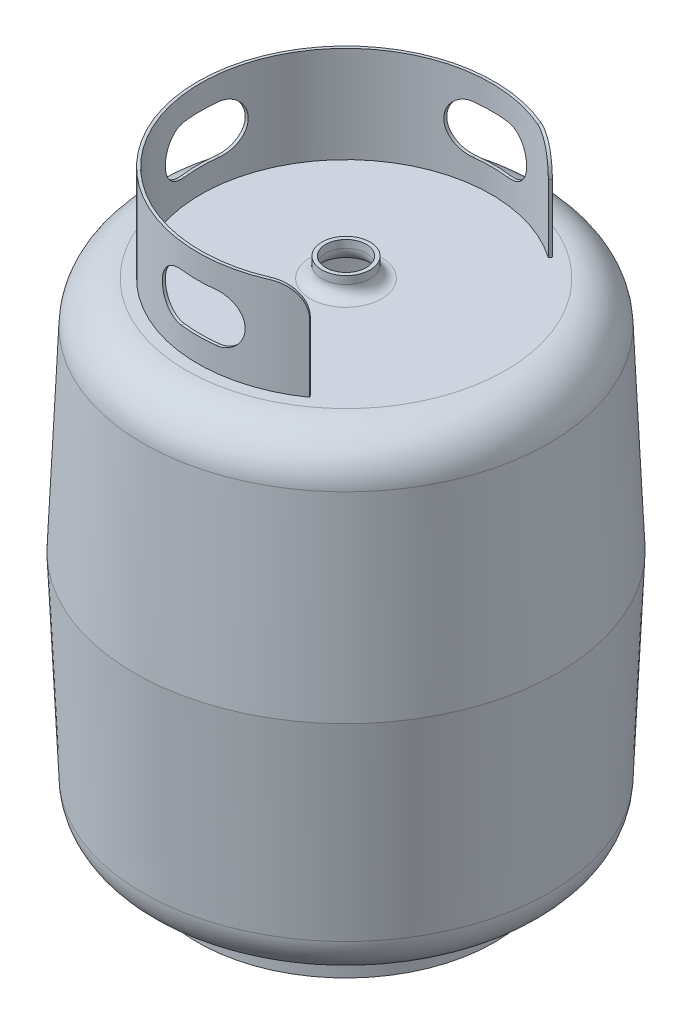
SolidWorks part; units mm, degrees
material "1060 Alloy"
ref_plane "Front Plane" through (0, 0, 0) normal (0, 0, 1) x (1, 0, 0)
ref_plane "Top Plane" through (0, 0, 0) normal (0, 1, 0) x (1, 0, 0)
ref_plane "Right Plane" through (0, 0, 0) normal (1, 0, 0) x (0, 0, -1)
sketch "Sketch1" plane through (0, 0, 0) normal (0, 0, 1) x (1, 0, 0)
  line L0 (0, -5395.1969) -> (0, 264364.6477) construction
  line L1 (0, 0) -> (165.6719, 0)
  line L2 (210.629, 43.0371) -> (219.4469, 245)
  line L3 (219.4469, 245) -> (210.629, 446.9629)
  line L4 (165.6719, 490) -> (37, 490)
  line L5 (25, 502) -> (25, 510)
  line L6 (0, 4) -> (165.6719, 4)
  line L7 (206.6328, 43.2116) -> (215.4431, 245)
  line L8 (215.4431, 245) -> (206.6328, 446.7884)
  line L9 (165.6719, 486) -> (37, 486)
  line L10 (21, 502) -> (21, 510)
  line L11 (21, 510) -> (25, 510)
  line L12 (0, 0) -> (0, 4)
  arc A0 (37, 490) -> (25, 502) centre (37, 502) cw
  arc A1 (165.6719, 0) -> (210.629, 43.0371) centre (165.6719, 45) ccw
  arc A2 (210.629, 446.9629) -> (165.6719, 490) centre (165.6719, 445) ccw
  arc A3 (165.6719, 4) -> (206.6328, 43.2116) centre (165.6719, 45) ccw
  arc A4 (206.6328, 446.7884) -> (165.6719, 486) centre (165.6719, 445) ccw
  arc A5 (37, 486) -> (21, 502) centre (37, 502) cw
  point P11 (25, 490)
  point P14 (208.75, 0)
  dimension "D8" = 12
  dimension "D9" = 45
  dimension "D1" = 208.75
  dimension "D2" = 490
  dimension "D3" = 245
  dimension "D4" = 20
  dimension "D5" = 25
  dimension "D6" = 92.5
  dimension "D7" = 92.5
  dimension "D10" = 4
revolve "Revolve1" add sketch "Sketch1" angle 360 about L0
sketch "Sketch3" plane through (0, 0, 0) normal (0, -1, 0) x (1, 0, 0)
  circle A0 centre (0, 0) radius 153.6719
  circle A1 centre (0, 0) radius 150.6719
  circle A2 centre (0, 0) radius 165.6719 construction
  dimension "D1" = 12
  dimension "D2" = 3
extrude "Boss-Extrude1" add sketch "Sketch3" along normal blind 30
sketch "Sketch4" plane through (0, 490, 0) normal (0, 1, 0) x (1, 0, 0)
  line L0 (0, 0) -> (88.1426, 125.8806) construction
  line L1 (88.1426, 125.8806) -> (0, 0) construction
  line L2 (0, 0) -> (165.6719, 0) construction
  line L3 (165.6719, 0) -> (0, 0) construction
  line L4 (0, 0) -> (88.1426, -125.8806) construction
  line L5 (88.1426, 125.8806) -> (86.4218, 123.4232)
  line L6 (86.4218, -123.4232) -> (88.1426, -125.8806)
  arc A0 (88.1426, 125.8806) -> (88.1426, -125.8806) centre (0, 0) ccw
  arc A1 (86.4218, 123.4232) -> (86.4218, -123.4232) centre (0, 0) ccw
  circle A2 centre (0, 0) radius 165.6719 construction
  point P3 (165.6719, 0)
  dimension "D1" = 12
  dimension "D2" = 3
  dimension "D3" = 55
  dimension "D4" = 55
extrude "Boss-Extrude2" add sketch "Sketch4" along normal blind 100
sketch "Sketch5" plane through (0, 0, 0) normal (0, 0, 1) x (1, 0, 0)
  line L0 (-18, 540) -> (18, 540) construction
  line L1 (-18, 565) -> (18, 565)
  line L2 (-18, 515) -> (18, 515)
  line L3 (0, 587.9417) -> (0, 229.5609) construction
  line L4 (86.4218, 590) -> (-150.6719, 590) construction
  arc A0 (-18, 565) -> (-18, 515) centre (-18, 540) ccw
  arc A1 (18, 515) -> (18, 565) centre (18, 540) ccw
  point P2 (0, 540)
  dimension "D1" = 36
  dimension "D2" = 50
  dimension "D3" = 50
extrude "Cut-Extrude1" cut sketch "Sketch5" against normal through all
pattern_circular "CirPattern1" count 4 over 360 about axis through (0, 245, 0) along (0, -1, 0) of "Cut-Extrude1"
fillet "Fillet1" radius 30 2 edges at (87.2822, 590, 124.6519) (87.2822, 590, -124.6519)
